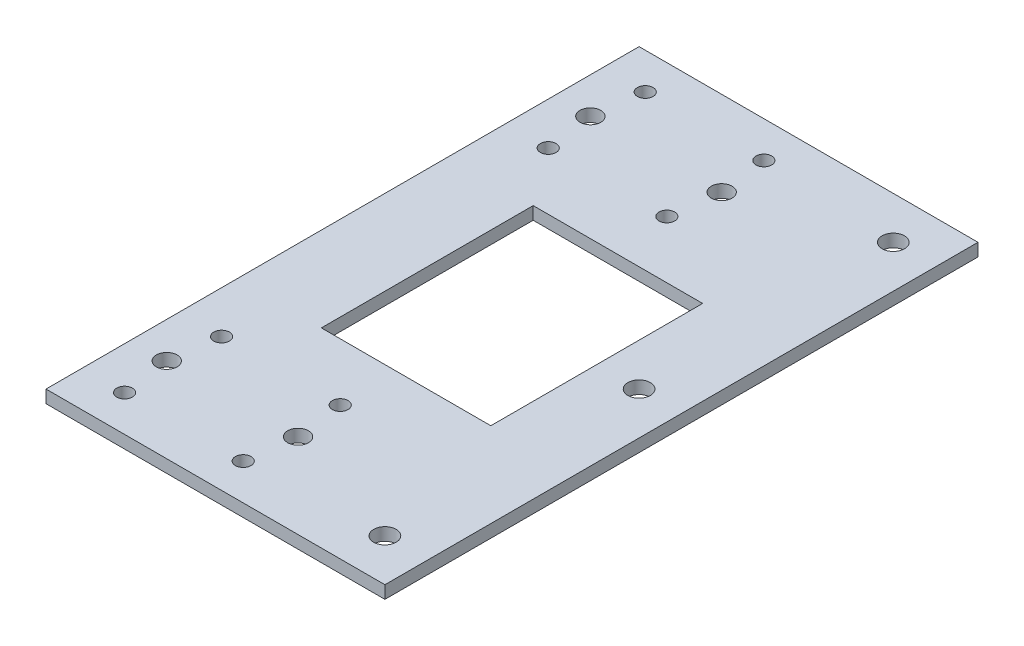
SolidWorks part; units mm, degrees
ref_plane "前视基准面" through (0, 0, 0) normal (0, 0, 1) x (1, 0, 0)
ref_plane "上视基准面" through (0, 0, 0) normal (0, 1, 0) x (1, 0, 0)
ref_plane "右视基准面" through (0, 0, 0) normal (1, 0, 0) x (0, 0, -1)
other "Configuration Table"
sketch "草图1" plane through (0, 0, 0) normal (0, 1, 0) x (1, 0, 0)
  line L0 (-40, 0) -> (49960, 0) construction
  line L1 (-40, -70) -> (40, -70)
  line L2 (-40, -70) -> (-40, 70)
  line L3 (-40, 70) -> (40, 70)
  line L4 (40, -70) -> (40, 70)
  line L5 (-40, -70) -> (40, 70) construction
  line L6 (-40, 70) -> (40, -70) construction
  line L7 (-40, 70) -> (8, 70)
  line L8 (-40, 70) -> (-40, 30)
  line L9 (-40, 30) -> (8, 30)
  line L10 (8, 70) -> (8, 30)
  line L11 (-40, -70) -> (8, -70)
  line L12 (-40, -70) -> (-40, -30)
  line L13 (-40, -30) -> (8, -30)
  line L14 (8, -70) -> (8, -30)
  line L15 (-40, 70) -> (-30, 70)
  line L16 (-40, 70) -> (-40, 61.45)
  line L17 (-40, 61.45) -> (-30, 61.45)
  line L18 (-30, 70) -> (-30, 61.45)
  line L19 (-16, 30) -> (-16, 50030) construction
  line L20 (8, 50) -> (-0.5, 50) construction
  line L22 (40, 70) -> (30, 70)
  line L23 (40, 70) -> (40, 60)
  line L24 (40, 60) -> (30, 60)
  line L25 (30, 70) -> (30, 60)
  circle A0 centre (-30, 61.45) radius 1.85
  circle A1 centre (-2, 61.45) radius 1.85
  circle A2 centre (-2, 38.55) radius 1.85
  circle A3 centre (-30, 38.55) radius 1.85
  circle A4 centre (-0.5, 50) radius 2.45
  circle A5 centre (-31.5, 50) radius 2.45
  circle A6 centre (-2, -38.55) radius 1.85
  circle A7 centre (-0.5, -50) radius 2.45
  circle A8 centre (-2, -61.45) radius 1.85
  circle A9 centre (-30, -38.55) radius 1.85
  circle A10 centre (-31.5, -50) radius 2.45
  circle A11 centre (-30, -61.45) radius 1.85
  circle A12 centre (30, 60) radius 2.5
  circle A13 centre (30, 0) radius 2.5
  circle A14 centre (30, -60) radius 2.5
  point P0 (0, 0)
  point P21 (-16, 30)
  point P33 (-40, 0)
  dimension "D9" = 3.7
  dimension "D11" = 4.9
  dimension "D14" = 5
  dimension "D1" = 80
  dimension "D2" = 140
  dimension "D3" = 40
  dimension "D4" = 48
  dimension "D5" = 48
  dimension "D6" = 40
  dimension "D7" = 10
  dimension "D8" = 8.55
  dimension "D10" = 8.5
  dimension "D12" = 10
  dimension "D13" = 10
  dimension "D15" = 3
extrude "凸台-拉伸1" add sketch "草图1" along normal blind 3 contours A12 L25 L3 L10 L9 L2 L13 L14 L1 L4 L24 A14 A13 | A12 L24 L4 L3 L25 | A0 L17 L2 L9 L10 L7 L18 A3 A2 A1 A4 A5 | A0 L18 L3 L8 L17 | L1 L14 L13 L2 A7 A6 A8 A9 A10 A11
sketch "草图2" plane through (0, 3, 0) normal (0, 1, 0) x (1, 0, 0)
  line L1 (20, -25) -> (-20, -25)
  line L2 (20, -25) -> (20, 25)
  line L3 (20, 25) -> (-20, 25)
  line L4 (-20, -25) -> (-20, 25)
  line L5 (20, -25) -> (-20, 25) construction
  line L6 (20, 25) -> (-20, -25) construction
  point P0 (0, 0)
  dimension "D1" = 40
  dimension "D2" = 50
extrude "切除-拉伸1" cut sketch "草图2" against normal up to next
sketch "草图3" plane through (0, 3, 0) normal (0, 1, 0) x (1, 0, 0)
  circle A0 centre (30, 60) radius 2.65
  circle A1 centre (30, 0) radius 2.65
  circle A2 centre (30, -60) radius 2.65
  dimension "D1" = 5.3
  dimension "D2" = 3
extrude "切除-拉伸2" cut sketch "草图3" against normal blind 10
